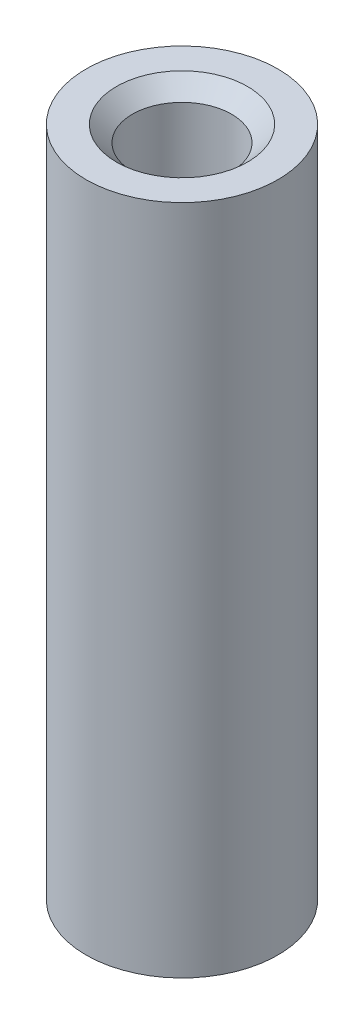
SolidWorks part; units mm, degrees
ref_plane "Ebene vorne" through (0, 0, 0) normal (0, 0, 1) x (1, 0, 0)
ref_plane "Ebene oben" through (0, 0, 0) normal (0, 1, 0) x (1, 0, 0)
ref_plane "Ebene rechts" through (0, 0, 0) normal (1, 0, 0) x (0, 0, -1)
sketch "Skizze1" plane through (0, 0, 0) normal (0, 1, 0) x (1, 0, 0)
  circle A0 centre (0, 0) radius 3
  circle A1 centre (0, 0) radius 1.55
  dimension "D1" = 6
  dimension "D2" = 3.1
extrude "Aufsatz-Linear austragen1" add sketch "Skizze1" along normal blind 21
chamfer "Fase1" distance 0.5 angle 45 2 edges at (0, 0, 1.55) (0, 21, 1.55)
